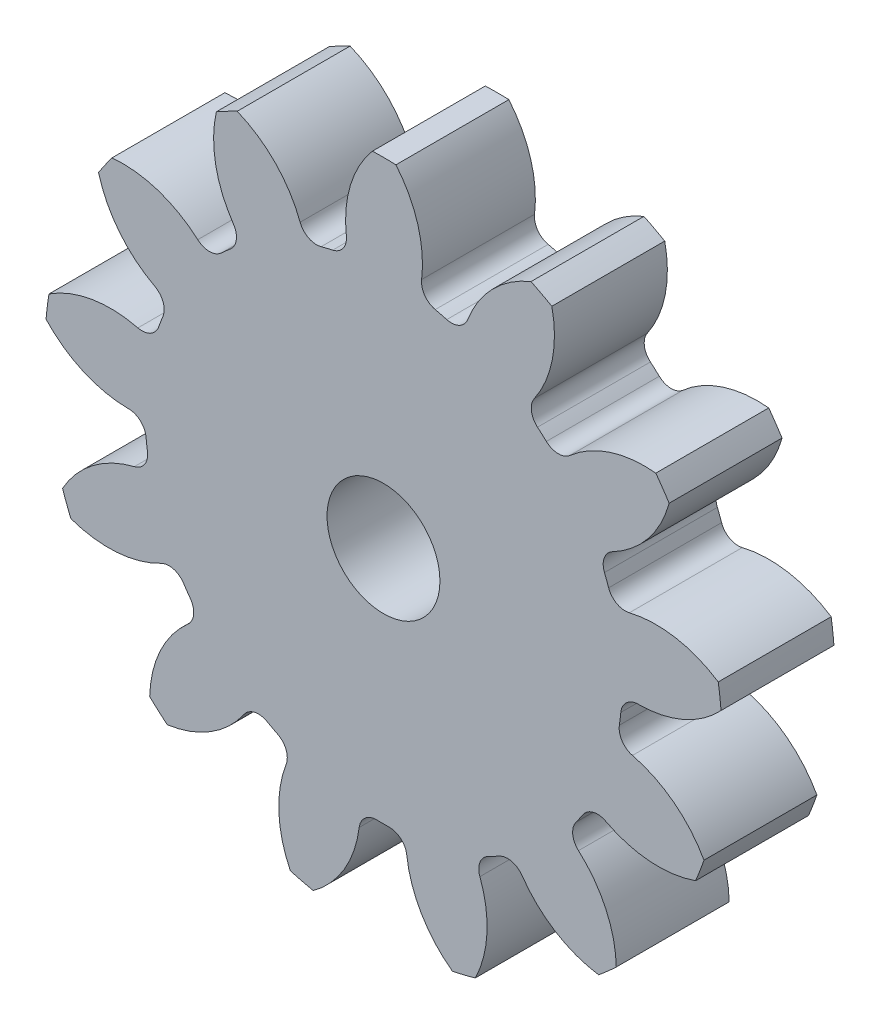
SolidWorks part; units mm, degrees
ref_plane "Front" through (0, 0, 0) normal (0, 0, 1) x (1, 0, 0)
ref_plane "Top" through (0, 0, 0) normal (0, 1, 0) x (1, 0, 0)
ref_plane "Right" through (0, 0, 0) normal (1, 0, 0) x (0, 0, -1)
sketch "Sketch3" plane through (0, 0, 0) normal (0, 0, 1) x (1, 0, 0)
  circle A0 centre (0, 0) radius 19.05
  dimension "od" = 38.1
extrude "gearBody" add sketch "Sketch3" along normal blind 6.35
sketch "Sketch2" plane through (0, 0, 0) normal (0, 0, 1) x (1, 0, 0)
  line L0 (0, 0) -> (14.3334, 5.9371) construction
  line L1 (18.4256, -7.0473) -> (0, 0) construction
  line L2 (0, 0) -> (36.3143, 0) construction
  line L3 (16.51, -0.0373) -> (16.0233, -3.9793) construction
  line L5 (16.2666, -2.0083) -> (0, 0) construction
  line L7 (0, 0) -> (15.5143, 0) construction
  arc A0 (15.5112, -0.3114) -> (15.1212, -3.4706) centre (0, 0) ccw construction
  arc A1 (18.9827, 1.5996) -> (18.0237, -6.1685) centre (0, 0) ccw construction
  arc A2 (16.51, -0.0373) -> (16.0233, -3.9793) centre (0, 0) ccw construction
  arc A3 (13.265, -1.9749) -> (13.347, -1.3106) centre (0, 0) ccw
  arc A4 (18.4256, -7.0473) -> (14.0008, -3.0762) centre (12.459, -9.2449) ccw
  arc A5 (18.4256, -7.0473) -> (19.5863, 2.3542) centre (0, 0) ccw
  arc A6 (19.5863, 2.3542) -> (14.3286, -0.4214) centre (14.3334, 5.9371) cw
  arc A7 (13.347, -1.3106) -> (14.3286, -0.4214) centre (14.3278, -1.4069) cw
  arc A8 (14.0008, -3.0762) -> (13.265, -1.9749) centre (14.2398, -2.1201) cw
  point P6 (19.5863, 2.3542)
  point P22 (18.4256, -7.0473)
  dimension "baseDia" = 31.0287
  dimension "od" = 38.1
  dimension "pd" = 33.02
  dimension "rd" = 26.8224
  dimension "rFillet" = 0.9855
  dimension "pointX" = 19.5863
  dimension "pointY" = 2.3542
  dimension "CTT" = 3.9421
  dimension "flankCenterAngle" = 22.5
extrude "toothCut" cut sketch "Sketch2" along normal through all
pattern_circular "CirPattern1" count 13 over 360 about axis through (0, 0, 0) along (0, 0, 1) of "toothCut"
sketch "hub1Dia" plane through (0, 0, 0) normal (0, 0, -1) x (-1, 0, 0)
  circle A0 centre (0, 0) radius 11.938
  dimension "hub1Dia" = 23.876
extrude "hub1" [suppressed] add sketch "hub1Dia" along normal blind 16.002
sketch "hub2Dia" plane through (0, 0, 6.35) normal (0, 0, 1) x (1, 0, 0)
  circle A0 centre (0, 0) radius 12.7
  dimension "hub2dia" = 25.4
sketch "boreDia" plane through (0, 0, 0) normal (0, 0, 1) x (1, 0, 0)
  circle A0 centre (0, 0) radius 3.175
  dimension "boreDia" = 6.35
extrude "bore" cut sketch "boreDia" against normal mid plane 25400
